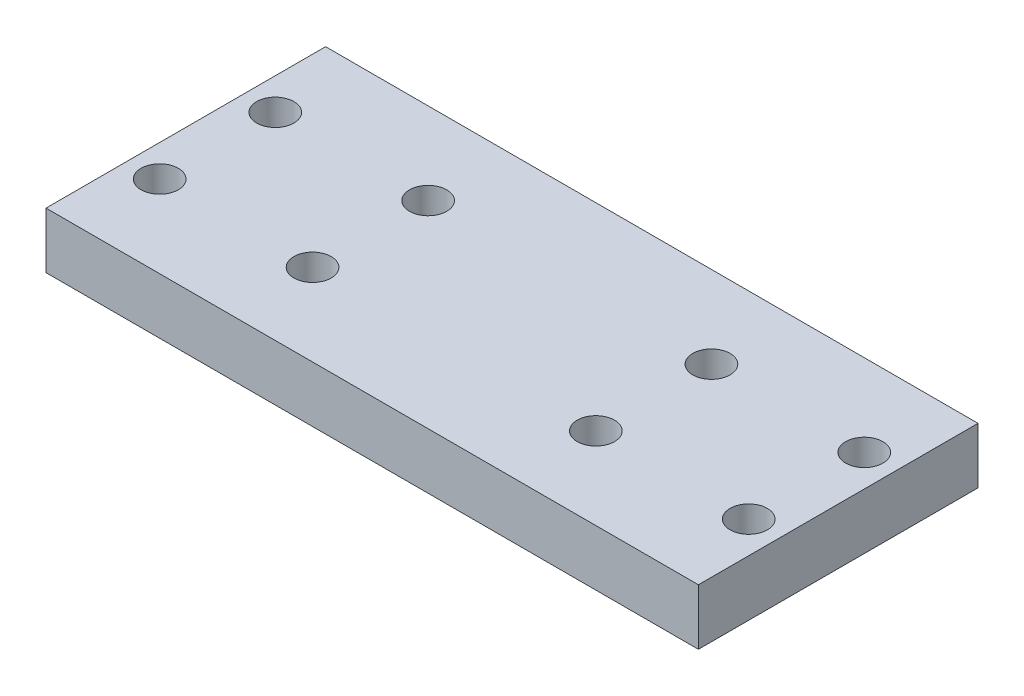
SolidWorks part; units mm, degrees
ref_plane "Front Plane" through (0, 0, 0) normal (0, 0, 1) x (1, 0, 0)
ref_plane "Top Plane" through (0, 0, 0) normal (0, 1, 0) x (1, 0, 0)
ref_plane "Right Plane" through (0, 0, 0) normal (1, 0, 0) x (0, 0, -1)
sketch "Sketch1" plane through (0, 0, 0) normal (0, 1, 0) x (1, 0, 0)
  line L0 (-235, 0) -> (115, 0) construction
  line L1 (115, -75) -> (-235, -75)
  line L2 (115, -75) -> (115, 75)
  line L3 (115, 75) -> (-235, 75)
  line L4 (-235, -75) -> (-235, 75)
  line L5 (-60, -75) -> (-60, 75) construction
  line L6 (-218, 31) -> (-136, 31) construction
  line L7 (-218, 31) -> (-218, -31) construction
  line L8 (-218, -31) -> (-136, -31) construction
  line L9 (-136, 31) -> (-136, -31) construction
  line L10 (-177, 31) -> (-177, 0) construction
  circle A0 centre (-218, 31) radius 10
  circle A1 centre (-136, 31) radius 10
  circle A2 centre (-136, -31) radius 10
  circle A3 centre (-218, -31) radius 10
  circle A4 centre (16, -31) radius 10
  circle A5 centre (16, 31) radius 10
  circle A6 centre (98, 31) radius 10
  circle A7 centre (98, -31) radius 10
  point P0 (0, 0)
  point P8 (-82.2265, 0)
  dimension "D1" = 350
  dimension "D2" = 150
  dimension "D3" = 82
  dimension "D4" = 76
  dimension "D5" = 62
  dimension "D6" = 31
extrude "Boss-Extrude1" add sketch "Sketch1" along normal blind 30
